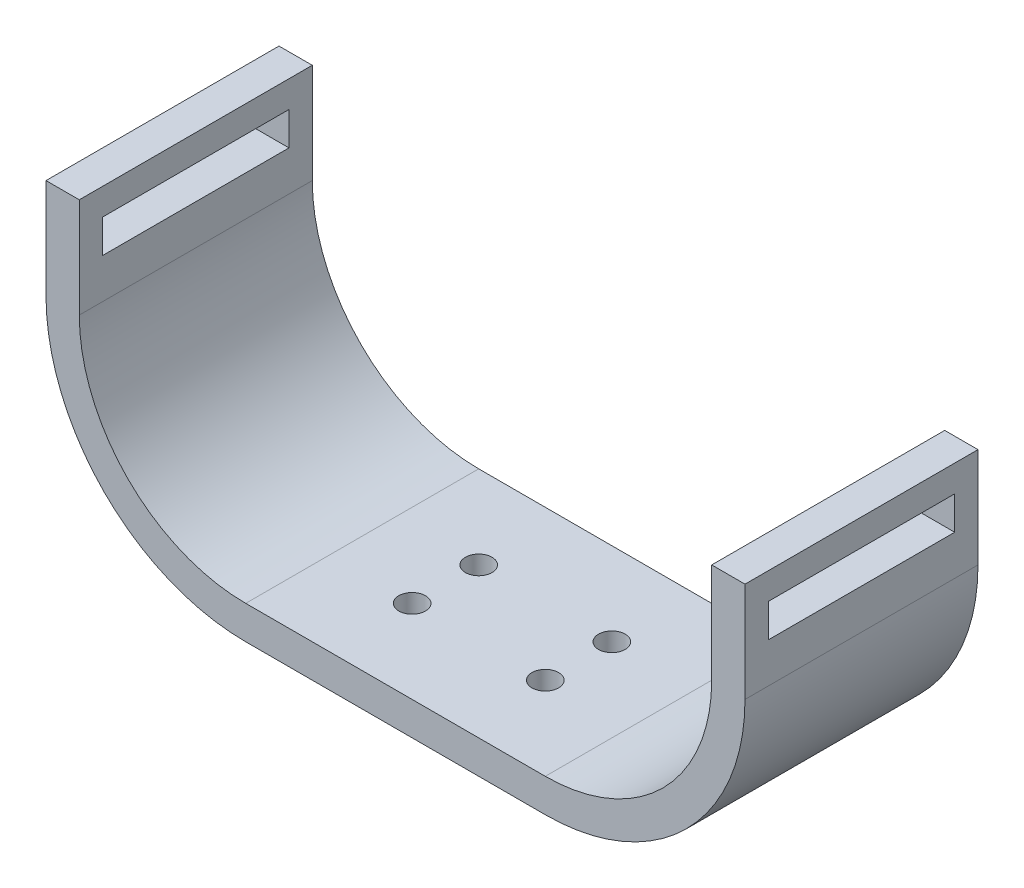
SolidWorks part; units mm, degrees
ref_plane "前视基准面" through (0, 0, 0) normal (0, 0, 1) x (1, 0, 0)
ref_plane "上视基准面" through (0, 0, 0) normal (0, 1, 0) x (1, 0, 0)
ref_plane "右视基准面" through (0, 0, 0) normal (1, 0, 0) x (0, 0, -1)
sketch "草图1" plane through (0, 0, 0) normal (0, 0, 1) x (1, 0, 0)
  line L0 (-52.5, 27.5) -> (-52.5, 42.5)
  line L1 (-22.5, -2.5) -> (22.5, -2.5)
  line L3 (-22.5, 2.5) -> (22.5, 2.5)
  line L5 (-22.5, -2.5) -> (22.5, 2.5) construction
  line L6 (-22.5, 2.5) -> (22.5, -2.5) construction
  line L7 (0, 2.5) -> (0, -2.5) construction
  line L8 (-52.5, 42.5) -> (-47.5, 42.5)
  line L9 (-47.5, 42.5) -> (-47.5, 27.5)
  line L10 (47.5, 42.5) -> (47.5, 27.5)
  line L11 (52.5, 42.5) -> (47.5, 42.5)
  line L12 (52.5, 27.5) -> (52.5, 42.5)
  arc A0 (-22.5, -2.5) -> (-52.5, 27.5) centre (-22.5, 27.5) cw
  arc A1 (-22.5, 2.5) -> (-47.5, 27.5) centre (-22.5, 27.5) cw
  arc A2 (22.5, -2.5) -> (52.5, 27.5) centre (22.5, 27.5) ccw
  arc A3 (22.5, 2.5) -> (47.5, 27.5) centre (22.5, 27.5) ccw
  point P0 (0, 0)
  dimension "D3" = 25
  dimension "D5" = 30
  dimension "D1" = 45
  dimension "D2" = 5
  dimension "D4" = 15
  dimension "D6" = 5
extrude "凸台-拉伸1" add sketch "草图1" along normal blind 35
sketch "草图3" plane through (52.5, 0, 0) normal (1, 0, 0) x (0, 0, -1)
  line L0 (-35, 42.5) -> (0, 42.5) construction
  line L1 (-31.5, 33.5) -> (-3.5, 33.5)
  line L2 (-31.5, 33.5) -> (-31.5, 38.5)
  line L3 (-31.5, 38.5) -> (-3.5, 38.5)
  line L4 (-3.5, 33.5) -> (-3.5, 38.5)
  line L5 (-31.5, 33.5) -> (-3.5, 38.5) construction
  line L6 (-31.5, 38.5) -> (-3.5, 33.5) construction
  line L7 (-35, 27.5) -> (-35, 42.5) construction
  point P0 (-17.5, 36)
  dimension "D1" = 5
  dimension "D2" = 6.5
  dimension "D3" = 17.5
  dimension "D4" = 14
extrude "切除-拉伸1" cut sketch "草图3" along direction (1, 0, 0) on the side against the normal through all
sketch "草图4" plane through (0, 2.5, 0) normal (0, 1, 0) x (1, 0, 0)
  line L0 (0, 0) -> (0, -35) construction
  line L1 (22.5, -35) -> (-22.5, -35) construction
  line L2 (22.5, 0) -> (-22.5, 0) construction
  circle A0 centre (-10, -12.5) radius 2
  circle A1 centre (-10, -22.5) radius 2
  circle A2 centre (10, -22.5) radius 2
  circle A3 centre (10, -12.5) radius 2
  dimension "D1" = 4
  dimension "D2" = 12.5
  dimension "D3" = 10
  dimension "D4" = 20
  dimension "D5" = 20
extrude "切除-拉伸2" cut sketch "草图4" against normal through all
